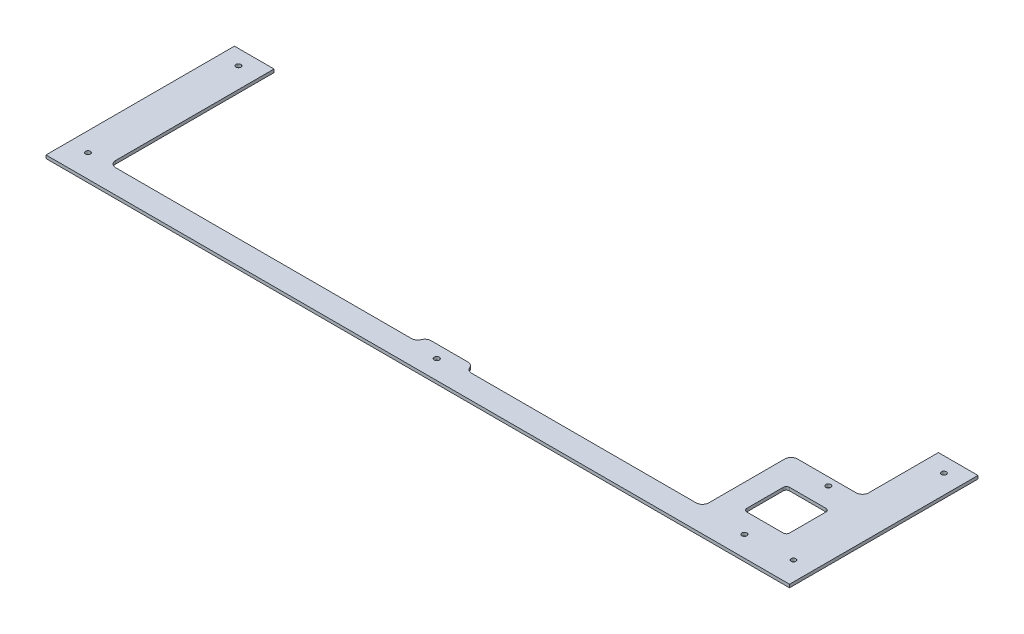
SolidWorks part; units mm, degrees
ref_plane "Alzado" through (0, 0, 0) normal (0, 0, 1) x (1, 0, 0)
ref_plane "Planta" through (0, 0, 0) normal (0, 1, 0) x (1, 0, 0)
ref_plane "Vista lateral" through (0, 0, 0) normal (1, 0, 0) x (0, 0, -1)
sketch "Croquis1" plane through (0, 0, 0) normal (0, 1, 0) x (1, 0, 0)
  line L0 (235.25, 120) -> (235.25, 0) construction
  line L1 (0, 0) -> (470.5, 0)
  line L2 (0, 0) -> (0, 120)
  line L3 (0, 120) -> (470.5, 120)
  line L4 (470.5, 0) -> (470.5, 120)
  line L5 (0, 60) -> (470.5, 60) construction
  circle A0 centre (12.5, 15) radius 1.55
  circle A1 centre (12.5, 110) radius 1.55
  circle A2 centre (458, 15) radius 1.55
  circle A3 centre (458, 110) radius 1.55
  dimension "D3" = 3.1
  dimension "D1" = 120
  dimension "D2" = 470.5
  dimension "D4" = 15
  dimension "D5" = 12.5
  dimension "D6" = 12.5
  dimension "D7" = 10
extrude "Saliente-Extruir1" add sketch "Croquis1" along normal blind 2
sketch "Croquis2" plane through (0, 0, 0) normal (0, -1, 0) x (1, 0, 0)
  line L0 (470, -0.5) -> (0.5, -0.5)
  line L1 (0.5, -0.5) -> (0.5, -119.5)
  line L2 (0.5, -119.5) -> (470, -119.5)
  line L3 (470, -119.5) -> (470, -0.5)
  line L4 (0, 0) -> (0, -120)
  line L5 (0, -120) -> (470.5, -120)
  line L6 (470.5, -120) -> (470.5, 0)
  line L7 (470.5, 0) -> (0, 0)
  line L8 (0, 0) -> (0, -120)
  line L9 (0, -120) -> (470.5, -120)
  line L10 (470.5, -120) -> (470.5, 0)
  line L11 (470.5, 0) -> (0, 0)
  dimension "D1" = 0
  dimension "D2" = 0.5
extrude "Cortar-Extruir1" cut sketch "Croquis2" against normal up to surface (2 mm away) up to face at (235.25, 2, -60)
sketch "Croquis3" plane through (0, 0, 0) normal (0, -1, 0) x (1, 0, 0)
  line L0 (235.25, -0.5) -> (235.25, -119.5) construction
  line L1 (470, -0.5) -> (0.5, -0.5) construction
  line L2 (0.5, -119.5) -> (470, -119.5) construction
  circle A0 centre (235.25, -12.5) radius 1.6
  dimension "D1" = 3.2
  dimension "D2" = 12
extrude "Cortar-Extruir2" cut sketch "Croquis3" against normal up to surface (2 mm away) up to face at (458, 2, -111.55)
sketch "Croquis4" plane through (0, 0, 0) normal (0, -1, 0) x (1, 0, 0)
  line L0 (470, -0.5) -> (0.5, -0.5) construction
  line L1 (450, -18.5) -> (407, -18.5)
  line L2 (450, -18.5) -> (450, -61.5)
  line L3 (450, -61.5) -> (407, -61.5)
  line L4 (407, -18.5) -> (407, -61.5)
  line L5 (470, -119.5) -> (470, -0.5) construction
  line L6 (407, -61.5) -> (450, -18.5) construction
  line L7 (428.5, -18.5) -> (428.5, -119.5) construction
  line L8 (415, -53.5) -> (442, -53.5)
  line L9 (415, -53.5) -> (415, -26.5)
  line L10 (415, -26.5) -> (442, -26.5)
  line L11 (442, -53.5) -> (442, -26.5)
  line L12 (415, -53.5) -> (442, -26.5) construction
  line L13 (415, -26.5) -> (442, -53.5) construction
  line L14 (0.5, -119.5) -> (470, -119.5) construction
  line L15 (428.5, -18.5) -> (428.5, -0.5) construction
  circle A0 centre (428.5, -66.5) radius 1.6
  circle A1 centre (428.5, -13.5) radius 1.6
  point P8 (428.5, -40)
  dimension "D7" = 3.2
  dimension "D1" = 43
  dimension "D2" = 43
  dimension "D3" = 18
  dimension "D4" = 20
  dimension "D5" = 27
  dimension "D6" = 27
  dimension "D8" = 5
  dimension "D9" = 5
extrude "Cortar-Extruir3" cut sketch "Croquis4" against normal up to surface (2 mm away) contours L9 L8 L11 L10 | A1 | A0 up to face at (235.25, 2, -14.1)
fillet "Redondeo1" radius 2 4 edges at (415, 1, -53.5) (442, 1, -53.5) (415, 1, -26.5) (442, 1, -26.5)
sketch "Croquis5" plane through (0, 0, 0) normal (0, -1, 0) x (1, 0, 0)
  line L0 (25.5, -119.5) -> (25.5, -15.5)
  line L1 (0.5, -119.5) -> (470, -119.5) construction
  line L2 (25.5, -15.5) -> (220.25, -15.5)
  line L3 (400, -15.5) -> (400, -71.5)
  line L4 (400, -71.5) -> (445, -71.5)
  line L5 (445, -71.5) -> (445, -119.5)
  line L6 (0.5, -0.5) -> (0.5, -119.5) construction
  line L7 (470, -119.5) -> (470, -0.5) construction
  line L8 (470, -0.5) -> (0.5, -0.5) construction
  line L9 (220.25, -15.5) -> (220.25, -20.5)
  line L10 (220.25, -20.5) -> (250.25, -20.5)
  line L11 (250.25, -20.5) -> (250.25, -15.5)
  line L12 (250.25, -15.5) -> (400, -15.5)
  line L13 (415, -51.5) -> (415, -28.5) construction
  line L14 (417, -53.5) -> (440, -53.5) construction
  line L15 (25.5, -119.5) -> (445, -119.5)
  circle A0 centre (235.25, -12.5) radius 1.6 construction
  dimension "D4" = 15
  dimension "D5" = 15
  dimension "D6" = 8
  dimension "D1" = 25
  dimension "D2" = 25
  dimension "D3" = 15
  dimension "D7" = 15
  dimension "D8" = 18
extrude "Cortar-Extruir4" cut sketch "Croquis5" against normal up to surface (2 mm away) up to face at (428.5, 2, -68.1)
fillet "Redondeo2" radius 4 6 edges at (445, 1, -71.5) (400, 1, -71.5) (400, 1, -15.5) (250.25, 1, -15.5) (220.25, 1, -15.5) (25.5, 1, -15.5)
fillet "Redondeo3" radius 4 2 edges at (220.25, 1, -20.5) (250.25, 1, -20.5)
sketch "Croquis6" plane through (0, 0, 0) normal (0, -1, 0) x (1, 0, 0)
  line L0 (466, -115.2447) -> (466, -28.2128)
  line L1 (442.2872, -4.5) -> (28.2128, -4.5)
  line L2 (4.5, -28.2128) -> (4.5, -115.5)
  line L3 (470, -119.5) -> (470, -0.5) construction
  line L4 (470, -0.5) -> (0.5, -0.5) construction
  line L5 (0.5, -0.5) -> (0.5, -119.5) construction
  line L6 (466, -115.2447) -> (466, -119.5)
  line L7 (445, -119.5) -> (470, -119.5) construction
  line L8 (466, -119.5) -> (4.5, -119.5)
  line L9 (0.5, -119.5) -> (25.5, -119.5) construction
  line L10 (4.5, -119.5) -> (4.5, -115.5)
  line L11 (441.4142, -27.0858) -> (415.5858, -52.9142) construction
  line L13 (406, -62.5) -> (449.9245, -62.5)
  line L14 (406, -62.5) -> (406, -16.3705)
  line L15 (406, -16.3705) -> (446.9321, -16.3705)
  line L16 (449.9245, -62.5) -> (449.9245, -20.0186)
  line L17 (406, -62.5) -> (441.4142, -27.0858) construction
  line L18 (406, -16.3705) -> (449.9245, -62.5) construction
  circle A0 centre (428.5, -66.5) radius 1.6 construction
  circle A1 centre (428.5, -13.5) radius 1.6 construction
  arc A2 (442.2872, -4.5) -> (446.9321, -16.3705) centre (470, -0.5) ccw
  arc A3 (442, -28.5) -> (440, -26.5) centre (440, -28.5) ccw construction
  circle A4 centre (458, -110) radius 1.55 construction
  circle A5 centre (235.25, -12.5) radius 1.6 construction
  arc A6 (415, -51.5) -> (417, -53.5) centre (417, -51.5) ccw construction
  circle A7 centre (12.5, -110) radius 1.55 construction
  arc A8 (449.9245, -20.0186) -> (466, -28.2128) centre (470, -0.5) ccw
  circle A36 centre (428.5, -66.5) radius 1.6
  circle A37 centre (428.5, -13.5) radius 1.6
  circle A38 centre (458, -110) radius 1.55
  circle A39 centre (235.25, -12.5) radius 1.6
  circle A42 centre (12.5, -110) radius 1.55
  arc A44 (4.5, -28.2128) -> (28.2128, -4.5) centre (0.5, -0.5) ccw
  point P20 (428.5, -40)
  point P21 (0.5, -0.5)
  dimension "D1" = 28
  dimension "D2" = 28
  dimension "D3" = 4
  dimension "D4" = 4
  dimension "D5" = 4
